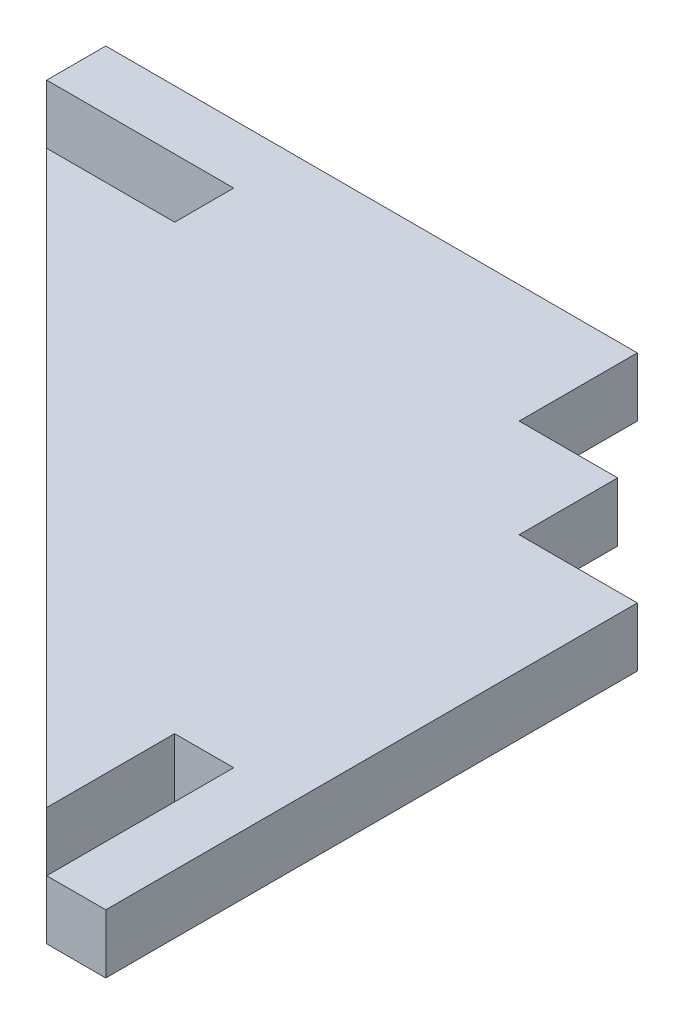
SolidWorks part; units mm, degrees
ref_plane "Front" through (0, 0, 0) normal (0, 0, 1) x (1, 0, 0)
ref_plane "Top" through (0, 0, 0) normal (0, 1, 0) x (1, 0, 0)
ref_plane "Right" through (0, 0, 0) normal (1, 0, 0) x (0, 0, -1)
sketch "Sketch2" plane through (0, 0, 0) normal (0, 1, 0) x (1, 0, 0)
  line L0 (0, 0) -> (-10, 0)
  line L1 (-70, 12) -> (12, -70)
  line L2 (0, -10) -> (0, 0)
  line L3 (-10, 0) -> (-10, 12)
  line L4 (-10, 12) -> (-70, 12)
  line L7 (12, -70) -> (12, -10)
  line L8 (12, -10) -> (0, -10)
  point P6 (0, 0)
  point P10 (6, -34.6797)
  point P11 (0, 0)
  point P12 (0, 0)
  point P13 (0, 0)
  dimension "D1" = 12
  dimension "D3" = 70
  dimension "D4" = 10
extrude "Boss-Extrude1" add sketch "Sketch2" along normal blind 6
sketch "Sketch3" plane through (0, 6, 0) normal (0, 1, 0) x (1, 0, 0)
  line L0 (-70, 12) -> (12, -70) construction
  line L1 (-64, 6) -> (-45, 6)
  line L2 (-64, 6) -> (-64, 0)
  line L3 (-64, 0) -> (-45, 0)
  line L4 (-45, 6) -> (-45, 0)
  line L5 (0, 0) -> (-10, 0) construction
  line L6 (6, -64) -> (0, -64)
  line L7 (6, -64) -> (6, -45)
  line L8 (6, -45) -> (0, -45)
  line L9 (0, -64) -> (0, -45)
  line L10 (0, -10) -> (0, 0) construction
  dimension "D1" = 6
  dimension "D2" = 45
extrude "Cut-Extrude1" cut sketch "Sketch3" against normal through all
sketch "Sketch4" plane through (0, 6, 0) normal (0, 1, 0) x (1, 0, 0)
  line L1 (-64, 6) -> (-70, 6)
  line L2 (-64, 6) -> (-64, 12)
  line L3 (-64, 12) -> (-70, 12)
  line L4 (-70, 6) -> (-70, 12)
  line L5 (6, -64) -> (12, -64)
  line L6 (6, -64) -> (6, -70)
  line L7 (6, -70) -> (12, -70)
  line L8 (12, -64) -> (12, -70)
extrude "Cut-Extrude2" cut sketch "Sketch4" against normal through all
